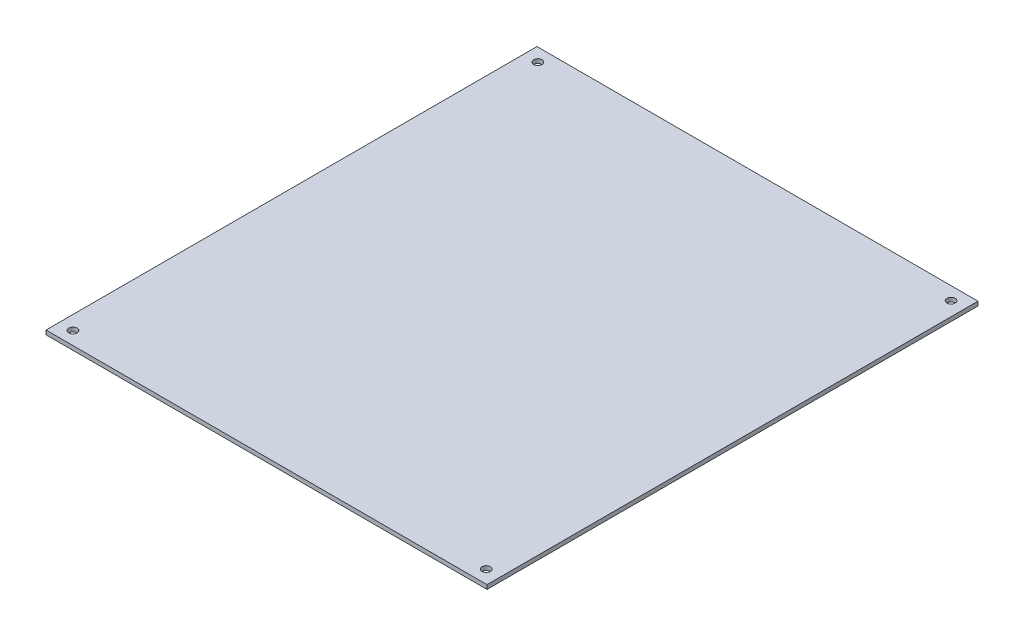
SolidWorks part; units mm, degrees
ref_plane "Front Plane" through (0, 0, 0) normal (0, 0, 1) x (1, 0, 0)
ref_plane "Top Plane" through (0, 0, 0) normal (0, 1, 0) x (1, 0, 0)
ref_plane "Right Plane" through (0, 0, 0) normal (1, 0, 0) x (0, 0, -1)
sketch "Sketch1" plane through (0, 0, 0) normal (0, 1, 0) x (1, 0, 0)
  line L1 (-106, -118) -> (106, -118)
  line L2 (-106, -118) -> (-106, 118)
  line L3 (-106, 118) -> (106, 118)
  line L4 (106, -118) -> (106, 118)
  line L5 (-106, -118) -> (106, 118) construction
  line L6 (-106, 118) -> (106, -118) construction
  point P0 (0, 0)
  dimension "D1" = 236
  dimension "D2" = 212
extrude "Boss-Extrude1" add sketch "Sketch1" along normal blind 2
sketch "Sketch2" plane through (0, 2, 0) normal (0, 1, 0) x (1, 0, 0)
  line L0 (0, 0) -> (-33218.1919, 37370.4659) construction
  line L1 (-96, -108) -> (96, -108) construction
  line L2 (-96, -108) -> (-96, 108) construction
  line L3 (-96, 108) -> (96, 108) construction
  line L4 (96, -108) -> (96, 108) construction
  line L5 (0, 0) -> (33218.1919, 37370.4659) construction
  circle A0 centre (99.3218, 111.737) radius 2
  circle A1 centre (-99.3218, 111.737) radius 2
  circle A2 centre (-99.3218, -111.737) radius 2
  circle A3 centre (99.3218, -111.737) radius 2
  point P0 (0, 0)
  dimension "D3" = 5
  dimension "D4" = 4
  dimension "D5" = 4
  dimension "D7" = 4
  dimension "D9" = 4
  dimension "D1" = 192
  dimension "D2" = 216
  dimension "D6" = 5
  dimension "D8" = 5
  dimension "D10" = 5
extrude "Cut-Extrude1" cut sketch "Sketch2" against normal through all
equation "\"Resolution Projector X\"= 1920"
equation "\"Resolution Projector Y\"= 1080"
equation "\"Resolution Build\"= 0.1"
equation "\"Size Build Volume X\"= \"Resolution Projector X\" * \"Resolution Build\""
equation "\"Size Build Volume Y\"= 2 * \"Resolution Projector Y\" * \"Resolution Build\""
equation "\"Size Build Volume Z\"= \"Size Build Volume Y\""
equation "\"Thick\"= 0.125in"
equation "\"Size Enclosure Internal X\"= 350mm"
equation "\"Size Enclosure Internal Y\"= \"Size Enclosure Internal X\""
equation "\"Size Enclosure Internal Z\"= \"Size Enclosure Internal X\""
equation "\"Size Enclosure External Z\"= 1000mm"
equation "\"Diameter Screw\"= 3mm"
equation "\"Diameter Nut\"= 5.5mm"
equation "\"Thick Nut\"= 2.5mm"
equation "\"Length Screw\"= 12mm"
equation "\"D1@Sketch1\"=\"Size Build Volume Y\"+20"
equation "\"D2@Sketch1\"=\"Size Build Volume X\"+20"
equation "\"D1@Sketch2\"=\"Size Build Volume X\""
equation "\"D2@Sketch2\"=\"Size Build Volume Y\""
